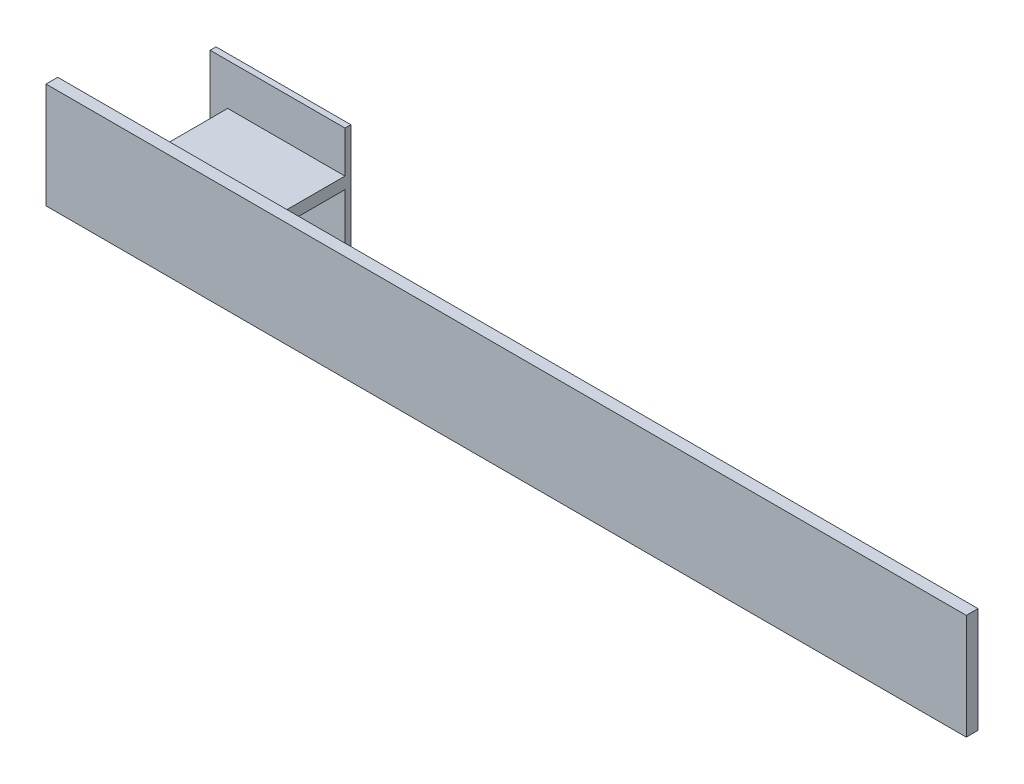
SolidWorks part; units mm, degrees
ref_plane "Front Plane" through (0, 0, 0) normal (0, 0, 1) x (1, 0, 0)
ref_plane "Top Plane" through (0, 0, 0) normal (0, 1, 0) x (1, 0, 0)
ref_plane "Right Plane" through (0, 0, 0) normal (1, 0, 0) x (0, 0, -1)
sketch "Sketch1" plane through (0, 0, 0) normal (0, 0, 1) x (1, 0, 0)
  line L1 (0, 0) -> (157, 0)
  line L2 (0, 0) -> (0, 18)
  line L3 (0, 18) -> (157, 18)
  line L4 (157, 0) -> (157, 18)
  dimension "D1" = 18
  dimension "D2" = 157
extrude "Boss-Extrude1" add sketch "Sketch1" along normal blind 2
sketch "Sketch2" plane through (0, 0, 0) normal (0, 0, -1) x (-1, 0, 0)
  line L1 (-12, 8.9) -> (-32, 8.9)
  line L2 (-12, 8.9) -> (-12, 10.9)
  line L3 (-12, 10.9) -> (-32, 10.9)
  line L4 (-32, 8.9) -> (-32, 10.9)
  line L5 (-12, 8.9) -> (-32, 10.9) construction
  line L6 (-12, 10.9) -> (-32, 8.9) construction
  line L8 (0, 18) -> (0, 0) construction
  point P0 (0, 0)
  point P7 (0, 0)
  dimension "D1" = 2
  dimension "D2" = 20
  dimension "D3" = 32
extrude "Boss-Extrude2" add sketch "Sketch2" along normal blind 17
sketch "Sketch3" plane through (0, 0, -17) normal (0, 0, -1) x (-1, 0, 0)
  line L0 (-32, 10.9) -> (-32, 8.9) construction
  line L1 (-32, 18) -> (-9, 18)
  line L2 (-32, 18) -> (-32, 0)
  line L3 (-32, 0) -> (-9, 0)
  line L4 (-9, 18) -> (-9, 0)
  line L5 (0, 0) -> (-157, 0) construction
  dimension "D1" = 18
  dimension "D2" = 23
  dimension "D3" = 0
  dimension "D4" = 0
extrude "Boss-Extrude3" add sketch "Sketch3" along normal blind 1
